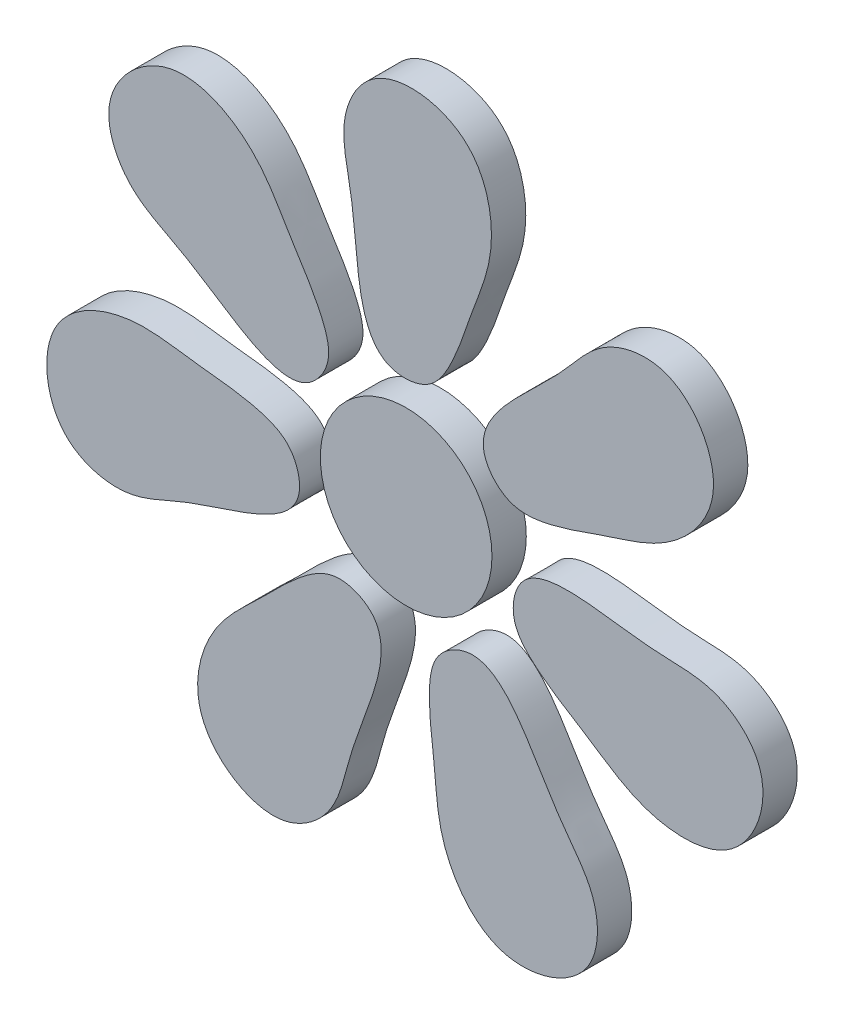
SolidWorks part; units mm, degrees
ref_plane "Спереди" through (0, 0, 0) normal (0, 0, 1) x (1, 0, 0)
ref_plane "Сверху" through (0, 0, 0) normal (0, 1, 0) x (1, 0, 0)
ref_plane "Справа" through (0, 0, 0) normal (1, 0, 0) x (0, 0, -1)
sketch "Эскиз1" plane through (0, 0, 0) normal (0, 0, 1) x (1, 0, 0)
  circle A0 centre (0, 0) radius 7.5
  dimension "D1" = 15
extrude "Бобышка-Вытянуть1" add sketch "Эскиз1" along normal blind 3
sketch "Эскиз2" plane through (0, 0, 0) normal (0, 0, 1) x (1, 0, 0)
  line L0 (0, 31.8975) -> (0, 9.6831) construction
  line L1 (0, 0) -> (0, 9.6831) construction
  spline S0 degree 3 poles (2.0385, 9.6624) (-3.2216, 9.4117) (-4.3712, 15.9966) (-4.6579, 21.256) (-6.0593, 26.5508) (-2.8642, 32.7962) (6.5836, 31.5866) (8.1212, 23.3147) (5.6367, 17.6094) (4.3479, 13.1951) (2.0385, 9.6624) (-3.2216, 9.4117) (-4.3712, 15.9966) knots -0.21505 -0.114805 -0.058658 0 0.119421 0.222513 0.306807 0.406804 0.546838 0.690237 0.78495 0.885195 0.941342 1 1.119421 1.222513 1.306807 only from (-1.5021, 9.9499) to (-1.5021, 9.9499)
  spline S1 degree 3 poles (8.8254, 4.4306) (5.3497, 8.3868) (9.7812, 13.3913) (13.7145, 16.8946) (16.9803, 21.2915) (23.8553, 22.6874) (28.8002, 14.5467) (23.2917, 8.1871) (17.2821, 6.5723) (13.0272, 4.8276) (8.8254, 4.4306) (5.3497, 8.3868) (9.7812, 13.3913) knots -0.21505 -0.114805 -0.058658 0 0.119421 0.222513 0.306807 0.406804 0.546838 0.690237 0.78495 0.885195 0.941342 1 1.119421 1.222513 1.306807 only from (6.8426, 7.3781) to (6.8426, 7.3781)
  spline S2 degree 3 poles (8.9666, -4.1375) (9.8926, 1.0466) (16.5682, 0.7021) (21.7596, -0.1888) (27.2334, -0.0007) (32.6112, -4.5055) (29.3297, -13.4472) (20.9231, -13.1056) (15.9136, -9.4139) (11.8968, -7.1751) (8.9666, -4.1375) (9.8926, 1.0466) (16.5682, 0.7021) knots -0.21505 -0.114805 -0.058658 0 0.119421 0.222513 0.306807 0.406804 0.546838 0.690237 0.78495 0.885195 0.941342 1 1.119421 1.222513 1.306807 only from (10.0347, -0.7496) to (10.0347, -0.7496)
  spline S3 degree 3 poles (2.3557, -9.59) (6.9862, -7.0818) (10.879, -12.5158) (13.4193, -17.13) (16.9792, -21.2924) (16.8102, -28.3056) (7.7733, -31.3151) (2.799, -24.5295) (2.5619, -18.3112) (1.8078, -13.7749) (2.3557, -9.59) (6.9862, -7.0818) (10.879, -12.5158) knots -0.21505 -0.114805 -0.058658 0 0.119421 0.222513 0.306807 0.406804 0.546838 0.690237 0.78495 0.885195 0.941342 1 1.119421 1.222513 1.306807 only from (5.6705, -8.3128) to (5.6705, -8.3128)
  spline S4 degree 3 poles (-6.029, -7.8211) (-1.181, -9.8774) (-3.0023, -16.309) (-5.026, -21.172) (-6.0607, -26.5505) (-11.6492, -30.791) (-19.6365, -25.602) (-17.4328, -17.4822) (-12.719, -13.4199) (-9.6425, -10.0019) (-6.029, -7.8211) (-1.181, -9.8774) (-3.0023, -16.309) knots -0.21505 -0.114805 -0.058658 0 0.119421 0.222513 0.306807 0.406804 0.546838 0.690237 0.78495 0.885195 0.941342 1 1.119421 1.222513 1.306807 only from (-2.9637, -9.6163) to (-2.9637, -9.6163)
  spline S5 degree 3 poles (-9.8738, -0.1627) (-8.4588, -5.2351) (-14.6228, -7.8212) (-19.6866, -9.271) (-24.5368, -11.8155) (-31.3366, -10.0902) (-32.2597, -0.6102) (-24.5373, 2.7295) (-18.4222, 1.5769) (-13.8318, 1.3028) (-9.8738, -0.1627) (-8.4588, -5.2351) (-14.6228, -7.8212) knots -0.21505 -0.114805 -0.058658 0 0.119421 0.222513 0.306807 0.406804 0.546838 0.690237 0.78495 0.885195 0.941342 1 1.119421 1.222513 1.306807 only from (-9.3662, -3.6785) to (-9.3662, -3.6785)
  spline S6 degree 3 poles (-6.2834, 7.6182) (-9.367, 3.3493) (-15.232, 6.5561) (-19.5228, 9.6112) (-24.5362, 11.8168) (-27.4269, 18.2088) (-20.5906, 24.8412) (-13.1647, 20.8859) (-10.2532, 15.3863) (-7.6054, 11.6264) (-6.2834, 7.6182) (-9.367, 3.3493) (-15.232, 6.5561) knots -0.21505 -0.114805 -0.058658 0 0.119421 0.222513 0.306807 0.406804 0.546838 0.690237 0.78495 0.885195 0.941342 1 1.119421 1.222513 1.306807 only from (-8.7157, 5.0293) to (-8.7157, 5.0293)
  point P77 (0, 0)
extrude "Бобышка-Вытянуть2" add sketch "Эскиз2" along normal blind 3 separate body
